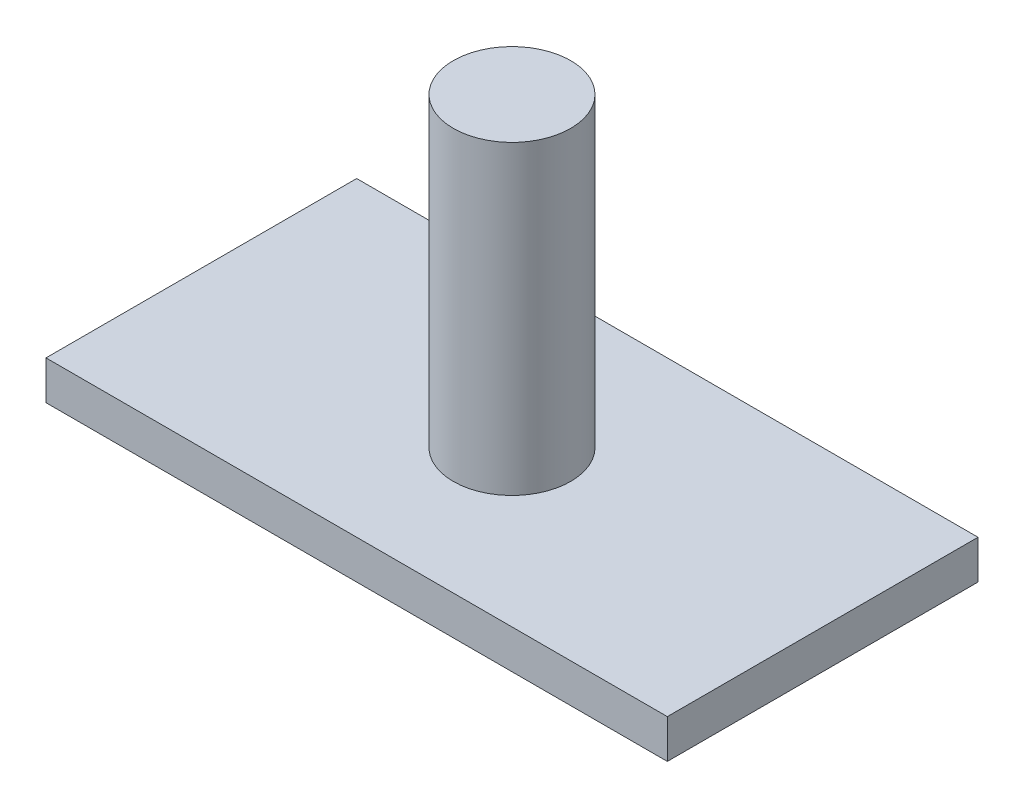
SolidWorks part; units mm, degrees
ref_plane "Front" through (0, 0, 0) normal (0, 0, 1) x (1, 0, 0)
ref_plane "Top" through (0, 0, 0) normal (0, 1, 0) x (1, 0, 0)
ref_plane "Right" through (0, 0, 0) normal (1, 0, 0) x (0, 0, -1)
sketch "Sketch1" plane through (0, 0, 0) normal (0, 1, 0) x (1, 0, 0)
  line L1 (0, 0) -> (50.8, 0)
  line L2 (0, 0) -> (0, 25.4)
  line L3 (0, 25.4) -> (50.8, 25.4)
  line L4 (50.8, 0) -> (50.8, 25.4)
  dimension "D1" = 25.4
  dimension "D2" = 50.8
extrude "Boss-Extrude1" add sketch "Sketch1" along normal blind 3.175
sketch "Sketch2" plane through (0, 3.175, 0) normal (0, 1, 0) x (1, 0, 0)
  line L0 (0, 25.4) -> (50.8, 0) construction
  circle A0 centre (25.4, 12.7) radius 4.8
  dimension "D1" = 9.6
extrude "Boss-Extrude2" add sketch "Sketch2" along normal blind 25
